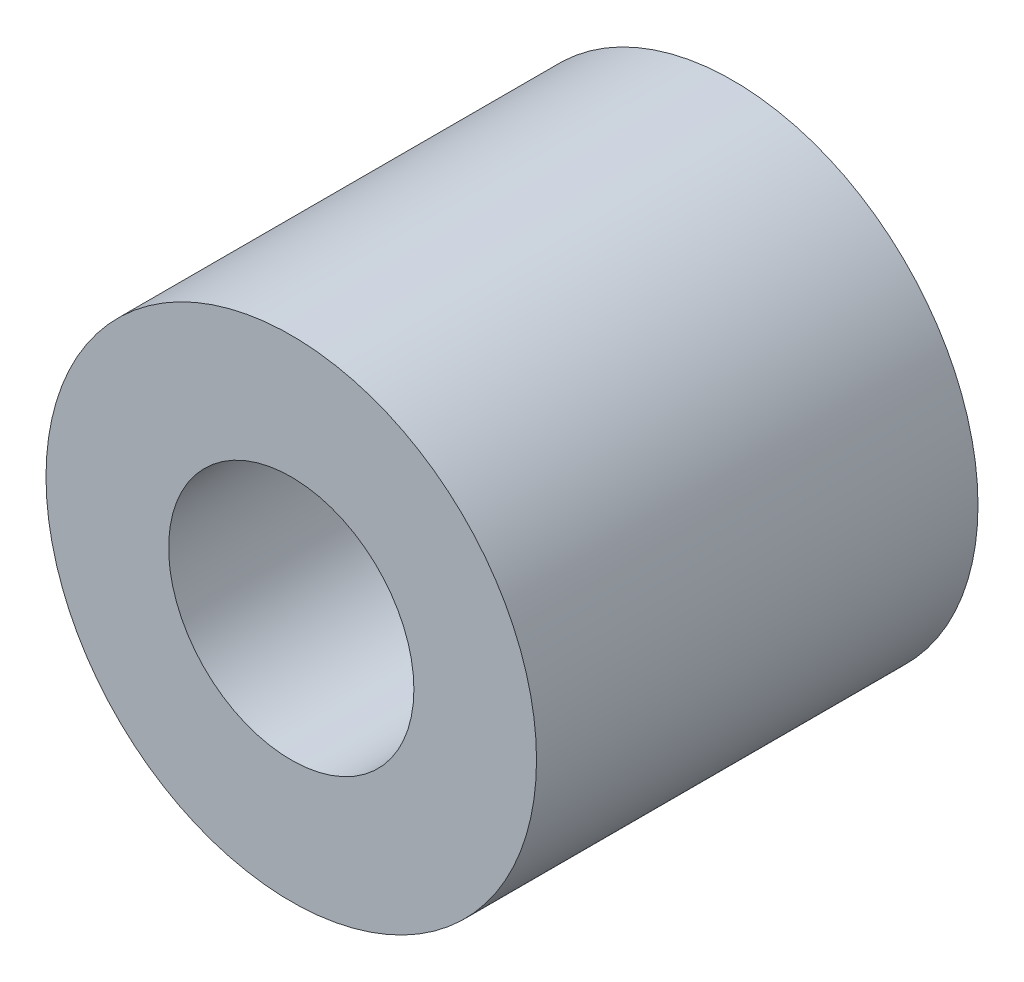
SolidWorks part; units mm, degrees
ref_plane "前视基准面" through (0, 0, 0) normal (0, 0, 1) x (1, 0, 0)
ref_plane "上视基准面" through (0, 0, 0) normal (0, 1, 0) x (1, 0, 0)
ref_plane "右视基准面" through (0, 0, 0) normal (1, 0, 0) x (0, 0, -1)
sketch "草图1" plane through (0, 0, 0) normal (0, 0, 1) x (1, 0, 0)
  circle A0 centre (0, 0) radius 2.5
  circle A1 centre (0, 0) radius 5
  dimension "D1" = 5
  dimension "D2" = 10
extrude "凸台-拉伸1" add sketch "草图1" along normal blind 9
